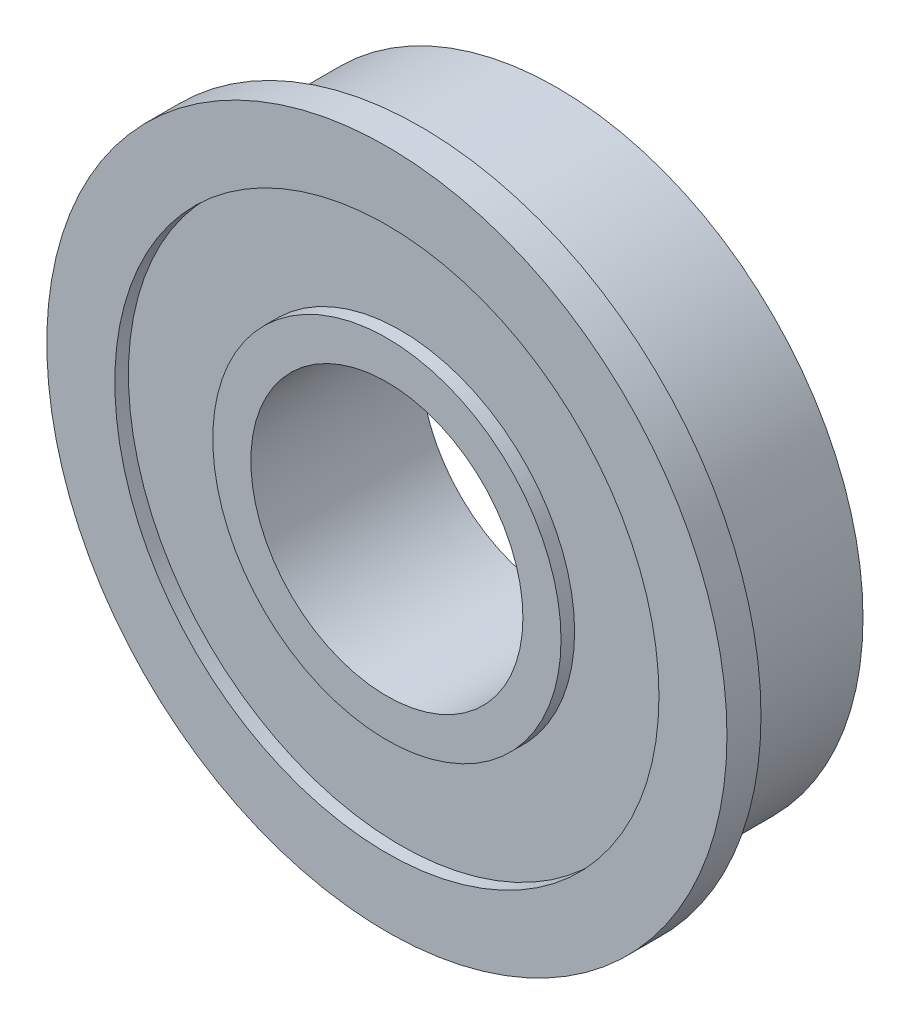
SolidWorks part; units mm, degrees
material "AISI 4130 Steel, annealed at 865C"
ref_plane "Front Plane" through (0, 0, 0) normal (0, 0, 1) x (1, 0, 0)
ref_plane "Top Plane" through (0, 0, 0) normal (0, 1, 0) x (1, 0, 0)
ref_plane "Right Plane" through (0, 0, 0) normal (1, 0, 0) x (0, 0, -1)
sketch "Sketch1" plane through (0, 0, 0) normal (0, 1, 0) x (1, 0, 0)
  line L0 (6.35, -3.9688) -> (8.128, -3.9688)
  line L1 (8.128, -3.9688) -> (8.128, -3.3338)
  line L2 (8.128, -3.3338) -> (12.7, -3.3338)
  line L3 (12.7, -3.3338) -> (12.7, -3.9688)
  line L4 (12.7, -3.9688) -> (15.875, -3.9688)
  line L5 (15.875, -3.9688) -> (15.875, -2.3813)
  line L6 (15.875, -2.3813) -> (14.2875, -2.3813)
  line L7 (14.2875, -2.3813) -> (14.2875, 3.9688)
  line L8 (14.2875, 3.9688) -> (12.7, 3.9688)
  line L9 (12.7, 3.9688) -> (12.7, 3.3338)
  line L10 (12.7, 3.3338) -> (8.128, 3.3338)
  line L11 (8.128, 3.3338) -> (8.128, 3.9688)
  line L12 (8.128, 3.9688) -> (6.35, 3.9688)
  line L13 (6.35, 3.9688) -> (6.35, -3.9688)
  line L14 (0, 3.9688) -> (0, -3.9688) construction
  dimension "D1" = 4.572
  dimension "D2" = 1.778
  dimension "D3" = 7.9375
  dimension "D4" = 1.5875
  dimension "D5" = 3.175
  dimension "D6" = 1.5875
revolve "Revolve1" add sketch "Sketch1" angle 360 about L14
